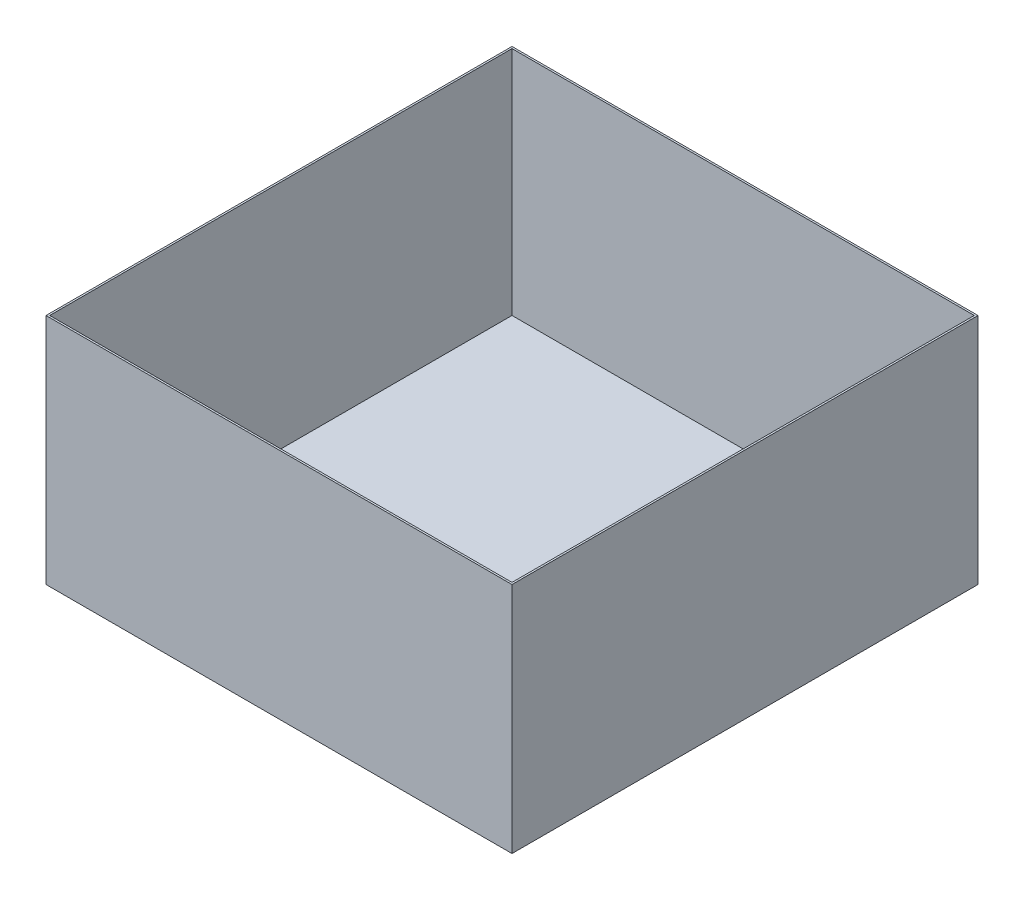
SolidWorks part; units mm, degrees
ref_plane "Front Plane" through (0, 0, 0) normal (0, 0, 1) x (1, 0, 0)
ref_plane "Top Plane" through (0, 0, 0) normal (0, 1, 0) x (1, 0, 0)
ref_plane "Right Plane" through (0, 0, 0) normal (1, 0, 0) x (0, 0, -1)
sketch "Sketch1" plane through (0, 0, 0) normal (0, 1, 0) x (1, 0, 0)
  line L1 (0, 0) -> (500, 0)
  line L2 (0, 0) -> (0, 500)
  line L3 (0, 500) -> (500, 500)
  line L4 (500, 0) -> (500, 500)
  dimension "D1" = 500
  dimension "D2" = 500
extrude "Boss-Extrude1" add sketch "Sketch1" against normal blind 250 contours L3 L4 L1 L2
shell "Shell1" thickness 2
